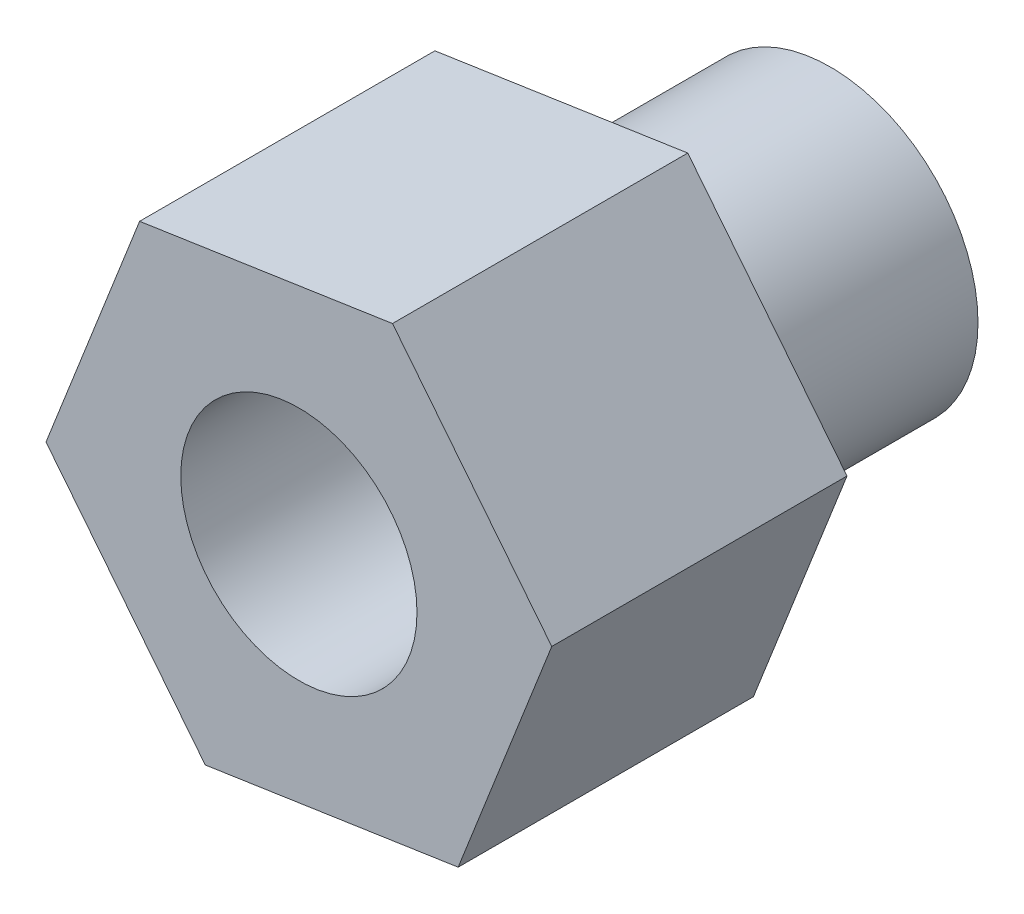
SolidWorks part; units mm, degrees
ref_plane "前视基准面" through (0, 0, 0) normal (0, 0, 1) x (1, 0, 0)
ref_plane "上视基准面" through (0, 0, 0) normal (0, 1, 0) x (1, 0, 0)
ref_plane "右视基准面" through (0, 0, 0) normal (1, 0, 0) x (0, 0, -1)
sketch "草图1" plane through (0, 0, 0) normal (0, 0, 1) x (1, 0, 0)
  circle A0 centre (0, 0) radius 5
  dimension "D1" = 10
extrude "拉伸1" add sketch "草图1" along normal blind 8
sketch "草图2" plane through (0, 0, 8) normal (0, 0, 1) x (1, 0, 0)
  line L1 (8.5645, 1.2841) -> (3.1702, 8.0591)
  line L2 (3.1702, 8.0591) -> (-5.3943, 6.7751)
  line L3 (-5.3943, 6.7751) -> (-8.5645, -1.2841)
  line L4 (-8.5645, -1.2841) -> (-3.1702, -8.0591)
  line L5 (-3.1702, -8.0591) -> (5.3943, -6.7751)
  line L6 (5.3943, -6.7751) -> (8.5645, 1.2841)
  circle A0 centre (0, 0) radius 7.5 construction
  dimension "D1" = 15
extrude "拉伸2" add sketch "草图2" along normal blind 10
sketch "草图3" plane through (0, 0, 18) normal (0, 0, 1) x (1, 0, 0)
  circle A0 centre (0, 0) radius 4
  dimension "D1" = 8
extrude "拉伸3" cut sketch "草图3" against normal through all
